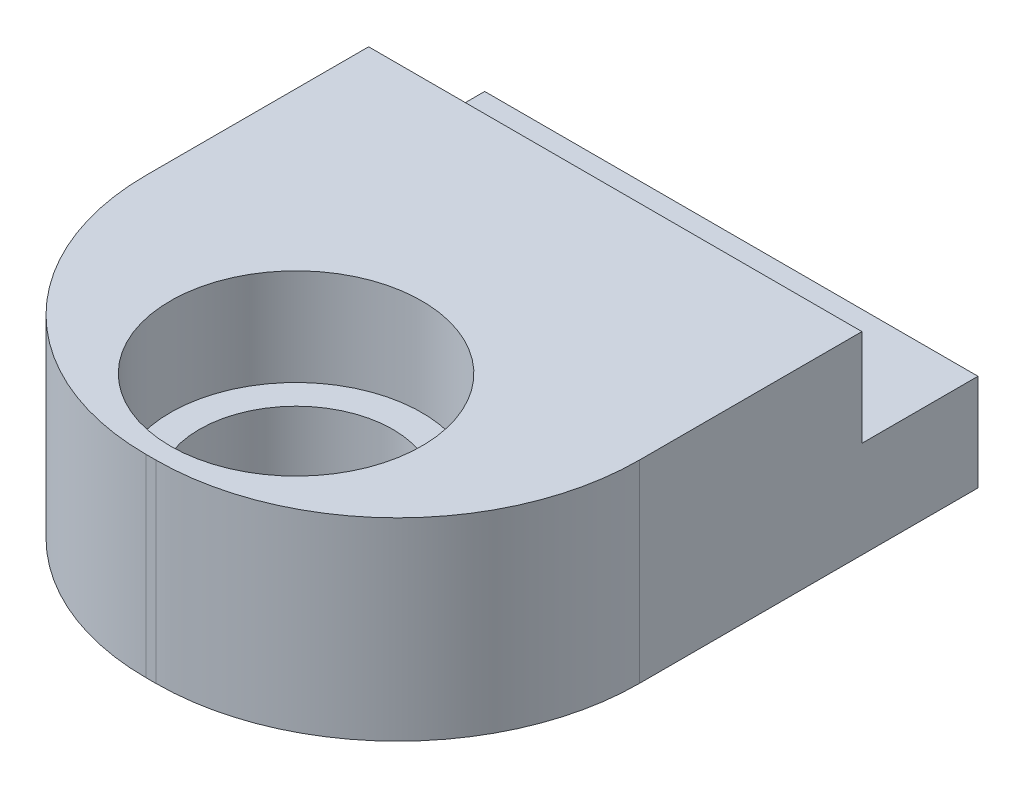
SolidWorks part; units mm, degrees
ref_plane "Płaszczyzna przednia" through (0, 0, 0) normal (0, 0, 1) x (1, 0, 0)
ref_plane "Płaszczyzna górna" through (0, 0, 0) normal (0, 1, 0) x (1, 0, 0)
ref_plane "Płaszczyzna prawa" through (0, 0, 0) normal (1, 0, 0) x (0, 0, -1)
sketch "Szkic1" plane through (0, 0, 0) normal (0, 1, 0) x (1, 0, 0)
  line L1 (25.5, -30) -> (-25.5, -30)
  line L2 (25.5, -30) -> (25.5, 30)
  line L3 (25.5, 30) -> (-25.5, 30)
  line L4 (-25.5, -30) -> (-25.5, 30)
  line L5 (25.5, -30) -> (-25.5, 30) construction
  line L6 (25.5, 30) -> (-25.5, -30) construction
  circle A0 centre (0, 24) radius 3.25
  circle A1 centre (0, -15) radius 10
  point P0 (0, 0)
  dimension "D3" = 6.5
  dimension "D4" = 20
  dimension "D1" = 51
  dimension "D2" = 6
  dimension "D5" = 15
  dimension "D6" = 60
extrude "Dodanie-wyciągnięcie1" add sketch "Szkic1" along normal blind 10
sketch "Szkic2" plane through (0, 0, 0) normal (0, 1, 0) x (1, 0, 0)
  line L0 (-25.5, 18) -> (25.5, 18)
  line L1 (-25.5, 30) -> (-25.5, -30) construction
  line L2 (25.5, -30) -> (25.5, 30) construction
  line L3 (25.5, 18) -> (25.5, -30)
  line L4 (25.5, -30) -> (-25.5, -30)
  line L5 (-25.5, -30) -> (-25.5, 18)
  line L6 (25.5, 30) -> (-25.5, 30) construction
  circle A0 centre (0, -15) radius 13
  dimension "D2" = 26
  dimension "D1" = 12
extrude "Dodanie-wyciągnięcie2" add sketch "Szkic2" along normal blind 10 from surface at 10 starting at face at (0, 10, -20.75)
fillet "Zaokrąglenie1" radius 25 2 edges at (25.5, 10, 30) (-25.5, 10, 30)
